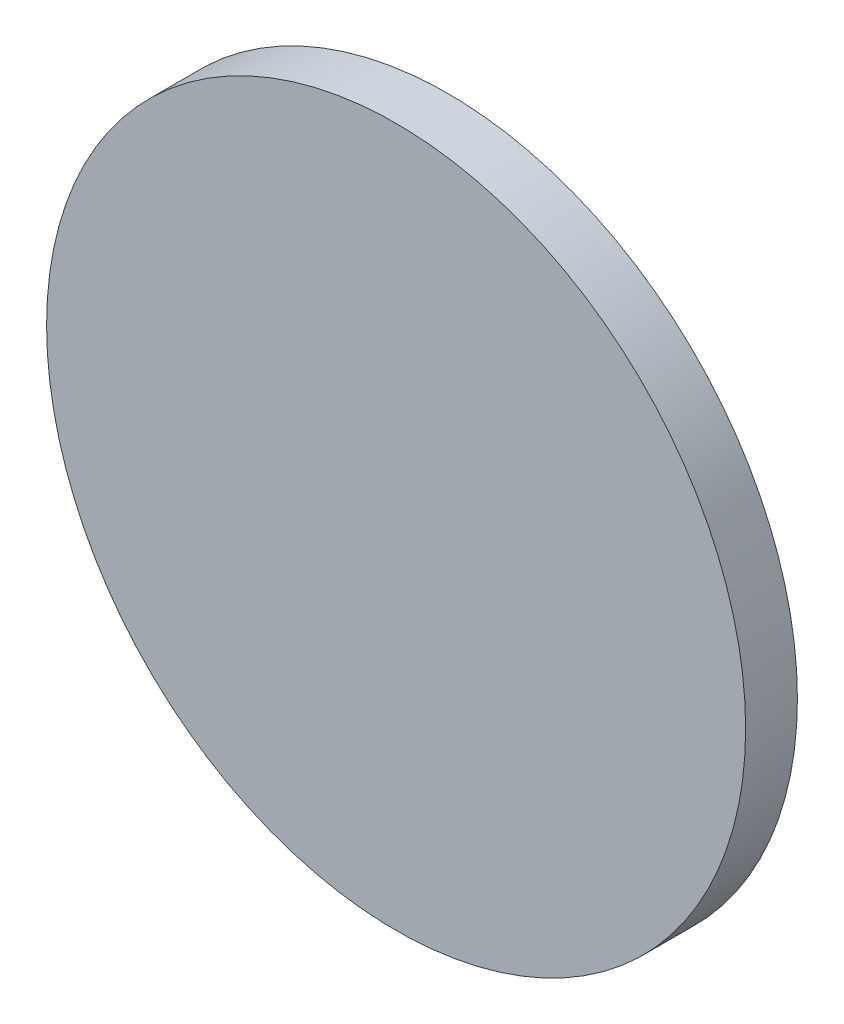
SolidWorks part; units mm, degrees
ref_plane "前视基准面" through (0, 0, 0) normal (0, 0, 1) x (1, 0, 0)
ref_plane "上视基准面" through (0, 0, 0) normal (0, 1, 0) x (1, 0, 0)
ref_plane "右视基准面" through (0, 0, 0) normal (1, 0, 0) x (0, 0, -1)
other "Configuration Table"
sketch "草图1" plane through (0, 0, 0) normal (0, 0, 1) x (1, 0, 0)
  circle A0 centre (0, 0) radius 27
  dimension "diameter" = 54
extrude "Yaw_Table" add sketch "草图1" along normal blind 4
